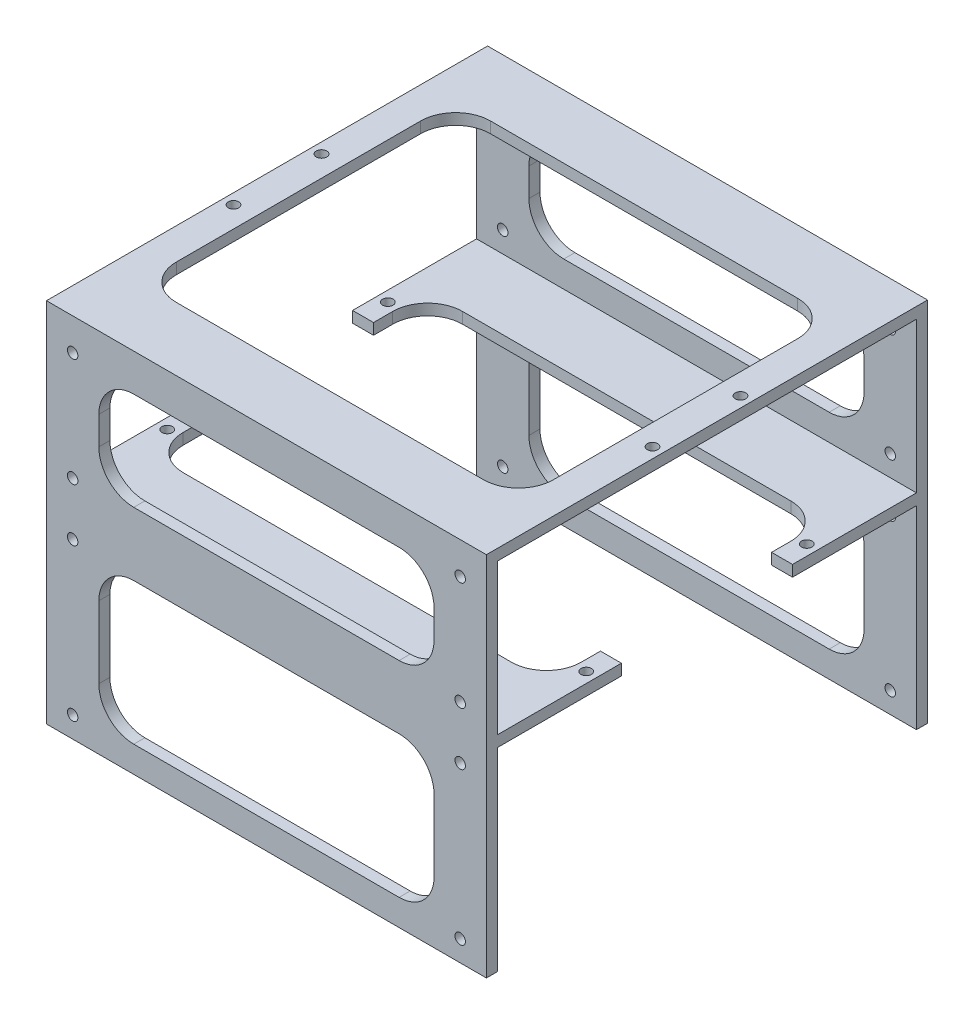
SolidWorks part; units mm, degrees
ref_plane "Front Plane" through (0, 0, 0) normal (0, 0, 1) x (1, 0, 0)
ref_plane "Top Plane" through (0, 0, 0) normal (0, 1, 0) x (1, 0, 0)
ref_plane "Right Plane" through (0, 0, 0) normal (1, 0, 0) x (0, 0, -1)
sketch "Sketch1" plane through (0, 0, 0) normal (1, 0, 0) x (0, 0, -1)
  line L0 (-95, 46.4295) -> (-95, -3.5705)
  line L1 (-43.5, 92.6795) -> (-95, 92.6795)
  line L3 (-43.5, 96.4295) -> (-100, 96.4295)
  line L4 (-100, 86.4295) -> (-100, 96.4295)
  line L5 (-100, 96.4295) -> (-90, 96.4295)
  line L6 (-100, 96.4295) -> (-100, -8.5705)
  line L7 (-100, -8.5705) -> (-90, -8.5705)
  line L8 (-95, 92.6795) -> (-95, 50.1795)
  line L9 (-95, 50.1795) -> (-59.5, 50.1795)
  line L11 (-95, 46.4295) -> (-59.5, 46.4295)
  line L12 (-59.5, 50.1795) -> (-59.5, 46.4295)
  line L13 (-90, -8.5705) -> (-35, -8.5705)
  line L15 (-95, -3.5705) -> (-35, -3.5705)
  line L16 (-35, -8.5705) -> (-35, -3.5705)
  line L18 (-43.5, 96.4295) -> (-35, 96.4295)
  line L20 (-43.5, 92.6795) -> (-35, 92.6795)
  line L21 (-35, 96.4295) -> (-35, 92.6795)
  dimension "D1" = 3.75
  dimension "D2" = 56.5
  dimension "D3" = 5
  dimension "D4" = 105
  dimension "D5" = 55
  dimension "D6" = 3.75
  dimension "D8" = 5
  dimension "D9" = 65
extrude "Boss-Extrude1" add sketch "Sketch1" along normal blind 126
sketch "Sketch2" plane through (0, 96.4295, 0) normal (0, 1, 0) x (1, 0, 0)
  line L0 (0, -35.75) -> (0, 35.75) construction
  line L1 (126, -35) -> (0, -35) construction
  circle A0 centre (3, -47.6) radius 1.5
  circle A1 centre (123, -47.6) radius 1.5
  dimension "D1" = 3
  dimension "D2" = 3
  dimension "D3" = 120
  dimension "D4" = 3
  dimension "D5" = 12.6
extrude "Cut-Extrude1" cut sketch "Sketch2" against normal up to surface (46.25 mm away) contours A1 | A0 up to face at (63, 50.1795, 77.25)
sketch "Sketch3" plane through (0, 50.1795, 0) normal (0, 1, 0) x (1, 0, 0)
  line L3 (126, -35) -> (126, -100) construction
  line L4 (0, -35.75) -> (0, 35.75) construction
  line L5 (126, -35) -> (0, -35) construction
  line L7 (6, -95) -> (6, -59.5)
  line L8 (6, -65) -> (6, -35)
  line L9 (16, -75) -> (110, -75)
  line L10 (120, -95) -> (120, -59.5)
  line L11 (120, -65) -> (120, -35)
  line L12 (6, -35) -> (120, -35)
  circle A0 centre (3, -66.6) radius 1.5
  circle A1 centre (123, -66.6) radius 1.5
  arc A3 (16, -75) -> (6, -65) centre (16, -65) cw
  arc A4 (110, -75) -> (120, -65) centre (110, -65) ccw
  circle A8 centre (3, -47.6) radius 1.5 construction
  dimension "D1" = 3
  dimension "D2" = 3
  dimension "D4" = 3
  dimension "D5" = 19
  dimension "D8" = 10
  dimension "D9" = 10
  dimension "D3" = 3
  dimension "D6" = 6
  dimension "D10" = 40
  dimension "D7" = 6
extrude "Cut-Extrude3" cut sketch "Sketch3" against normal up to surface (53.75 mm away) contours A0 | A1 | L11 L12 L8 A3 L9 A4 up to face at (63, -3.5705, 65)
ref_plane "Plane1" through (0, 0, 35) normal (0, 0, -1) x (-1, 0, 0)
mirror "Mirror2" about plane through (0, 0, 35) normal (0, 0, -1) of "Cut-Extrude1", "Cut-Extrude3", "Boss-Extrude1"
sketch "Sketch4" plane through (0, 96.4295, 0) normal (0, 1, 0) x (1, 0, 0)
  line L0 (9, -35) -> (9, -70)
  line L2 (19, -80) -> (106.9997, -80)
  line L3 (116.9997, -70) -> (116.9997, -35)
  line L4 (9, -35) -> (116.9997, -35)
  line L5 (63, -100) -> (62.9998, -80) construction
  line L6 (9, -35) -> (116.9997, -35)
  line L7 (126, -100) -> (0, -100) construction
  line L9 (126, -35) -> (0, -35) construction
  line L10 (126, -100) -> (126, 30) construction
  line L11 (0, -57.75) -> (0, 57.75) construction
  line L12 (55, -35) -> (-55, -35) construction
  circle A0 centre (3, -47.6) radius 1.5 construction
  arc A2 (106.9997, -80) -> (116.9997, -70) centre (106.9997, -70) ccw
  arc A3 (19, -80) -> (9, -70) centre (19, -70) cw
  dimension "D1" = 6
  dimension "D4" = 10
  dimension "D2" = 45
extrude "Cut-Extrude6" cut sketch "Sketch4" against normal up to surface (46.25 mm away) contours L4 L3 A2 L2 A3 L0 up to face at (3, 50.1795, 68.1)
mirror "Mirror5" about plane through (0, 0, 35) normal (0, 0, -1) of "Cut-Extrude6"
sketch "Sketch5" plane through (126, 0, 0) normal (1, 0, 0) x (0, 0, -1)
  line L0 (-35, 96.4295) -> (-35, 93.2545) construction
  line L1 (-100, 96.4295) -> (30, 96.4295) construction
  line L2 (-100, -8.5705) -> (30, -8.5705) construction
  line L3 (-95, 46.4295) -> (-95, -3.5705) construction
  line L4 (-95, -3.5705) -> (25, -3.5705)
  line L5 (-95, -3.5705) -> (-95, -8.5705)
  line L6 (-95, -8.5705) -> (25, -8.5705)
  line L8 (-100, 96.4295) -> (-98.175, 96.4295)
  line L9 (-100, 96.4295) -> (-100, -8.5705)
  line L10 (-100, -8.5705) -> (-98.175, -8.5705)
  line L11 (-98.175, 93.2545) -> (-98.175, -8.5705)
  line L12 (-59.5, 50.1795) -> (-59.5, 46.4295) construction
  line L13 (-95, 92.6795) -> (25, 92.6795)
  line L14 (-95, 92.6795) -> (-95, 93.2545)
  line L15 (-95, 93.2545) -> (25, 93.2545)
  line L17 (-95, 46.4295) -> (-59.5, 46.4295)
  line L18 (-95, 46.4295) -> (-95, 47.0045)
  line L19 (-95, 47.0045) -> (-59.5, 47.0045)
  line L20 (-59.5, 46.4295) -> (-59.5, 47.0045)
  line L21 (-95, 50.1795) -> (-59.5, 50.1795) construction
  line L22 (25, 92.6795) -> (25, 93.2545)
  line L23 (25, -3.5705) -> (25, -8.5705)
  line L24 (-10.5, 46.4295) -> (-10.5, 47.0045)
  line L25 (25, 47.0045) -> (-10.5, 47.0045)
  line L26 (25, 46.4295) -> (25, 47.0045)
  line L27 (25, 46.4295) -> (-10.5, 46.4295)
  line L28 (28.175, 93.2545) -> (28.175, -8.5705)
  line L29 (30, -8.5705) -> (28.175, -8.5705)
  line L30 (30, 96.4295) -> (30, -8.5705)
  line L31 (30, 96.4295) -> (28.175, 96.4295)
  line L32 (-35, 92.6795) -> (-35, -3.5705) construction
  line L33 (-98.175, 93.2545) -> (-97.175, 93.2545)
  line L43 (28.175, 96.4295) -> (27.175, 96.4295)
  line L45 (28.175, 93.2545) -> (27.175, 93.2545)
  line L46 (27.175, 96.4295) -> (27.175, 93.2545)
  line L47 (-97.175, 96.4295) -> (-97.175, 93.2545)
  line L48 (-98.175, 96.4295) -> (-97.175, 96.4295)
  dimension "D1" = 3.175
  dimension "D2" = 3.175
  dimension "D3" = 3.175
  dimension "D4" = 1
extrude "Cut-Extrude7" cut sketch "Sketch5" against normal through all
sketch "Sketch6" plane through (0, 0, 95) normal (0, 0, -1) x (-1, 0, 0)
  line L0 (-62.9998, 93.2545) -> (-63, 50.1795) construction
  line L1 (-106.9997, 93.2545) -> (-19, 93.2545) construction
  line L2 (-126, 50.1795) -> (0, 50.1795) construction
  line L3 (0, 93.2545) -> (-126, 93.2545) construction
  line L4 (-100.9998, 85.7545) -> (-25, 85.7545)
  line L5 (-110.9998, 75.7545) -> (-110.9998, 67.6795)
  line L6 (-100.9998, 57.6795) -> (-25, 57.6795)
  line L7 (-15, 75.7545) -> (-15, 67.6795)
  line L8 (-110.9998, 85.7545) -> (-15, 57.6795) construction
  line L9 (-110.9998, 57.6795) -> (-15, 85.7545) construction
  line L10 (0, 93.2545) -> (0, 50.1795) construction
  line L11 (-63, 47.0045) -> (-63, -8.5705) construction
  line L12 (-110, 47.0045) -> (-16, 47.0045) construction
  line L13 (0, -8.5705) -> (-126, -8.5705) construction
  line L14 (0, 47.0045) -> (0, -8.5705) construction
  line L15 (-101, 39.5045) -> (-25, 39.5045)
  line L16 (-111, 29.5045) -> (-111, 8.9295)
  line L17 (-101, -1.0705) -> (-25, -1.0705)
  line L18 (-15, 29.5045) -> (-15, 8.9295)
  line L19 (-111, 39.5045) -> (-15, -1.0705) construction
  line L20 (-111, -1.0705) -> (-15, 39.5045) construction
  line L21 (0, 47.0045) -> (-126, 47.0045) construction
  arc A0 (-25, 39.5045) -> (-15, 29.5045) centre (-25, 29.5045) cw
  arc A1 (-25, -1.0705) -> (-15, 8.9295) centre (-25, 8.9295) ccw
  arc A2 (-111, 8.9295) -> (-101, -1.0705) centre (-101, 8.9295) ccw
  arc A3 (-101, 39.5045) -> (-111, 29.5045) centre (-101, 29.5045) ccw
  arc A4 (-110.9998, 67.6795) -> (-100.9998, 57.6795) centre (-100.9998, 67.6795) ccw
  arc A5 (-100.9998, 85.7545) -> (-110.9998, 75.7545) centre (-100.9998, 75.7545) ccw
  arc A6 (-25, 57.6795) -> (-15, 67.6795) centre (-25, 67.6795) ccw
  arc A7 (-25, 85.7545) -> (-15, 75.7545) centre (-25, 75.7545) cw
  point P6 (-62.9999, 71.717)
  point P21 (-63, 19.217)
  dimension "D5" = 10
  dimension "D1" = 7.5
  dimension "D2" = 15
  dimension "D3" = 15
  dimension "D4" = 7.5
extrude "Cut-Extrude8" cut sketch "Sketch6" against normal through all and the other way through all
sketch "Sketch7" plane through (0, 0, 98.175) normal (0, 0, 1) x (1, 0, 0)
  line L0 (63, 93.2545) -> (63, -1.0705) construction
  line L1 (0, 93.2545) -> (126, 93.2545) construction
  line L2 (101, -1.0705) -> (25, -1.0705) construction
  line L3 (118.5, 93.2545) -> (118.5, -8.5705) construction
  line L5 (126, 93.2545) -> (126, 50.1795) construction
  line L6 (0, -8.5705) -> (126, -8.5705) construction
  line L7 (126, 50.1795) -> (0, 50.1795) construction
  line L8 (110, 47.0045) -> (120, 47.0045) construction
  line L9 (7.5, 93.2545) -> (7.5, -8.5705) construction
  circle A0 centre (118.5, 87.2545) radius 1.5
  circle A1 centre (118.5, 56.1795) radius 1.5
  circle A2 centre (118.5, 41.0045) radius 1.5
  circle A3 centre (118.5, -2.5705) radius 1.5
  circle A4 centre (7.5, -2.5705) radius 1.5
  circle A5 centre (7.5, 41.0045) radius 1.5
  circle A6 centre (7.5, 56.1795) radius 1.5
  circle A7 centre (7.5, 87.2545) radius 1.5
  dimension "D2" = 6
  dimension "D3" = 3
  dimension "D5" = 3
  dimension "D7" = 3
  dimension "D8" = 3
  dimension "D1" = 7.5
  dimension "D4" = 6
  dimension "D6" = 6
  dimension "D9" = 6
extrude "Cut-Extrude9" cut sketch "Sketch7" against normal through all and the other way through all
sketch "Sketch8" plane through (126, 0, 0) normal (1, 0, 0) x (0, 0, -1)
  line L0 (-97.175, 96.4295) -> (-97.175, 93.2545)
  line L1 (-97.175, 93.2545) -> (-98.175, 93.2545)
  line L2 (-98.175, 93.2545) -> (-98.175, 96.4295)
  line L3 (-98.175, 96.4295) -> (-97.175, 96.4295)
  line L4 (28.175, 93.2545) -> (27.175, 93.2545)
  line L5 (27.175, 93.2545) -> (27.175, 96.4295)
  line L6 (27.175, 96.4295) -> (28.175, 96.4295)
  line L7 (28.175, 96.4295) -> (28.175, 93.2545)
extrude "Boss-Extrude2" add sketch "Sketch8" against normal up to surface (126 mm away) up to face at (0, 55.342, 35)
